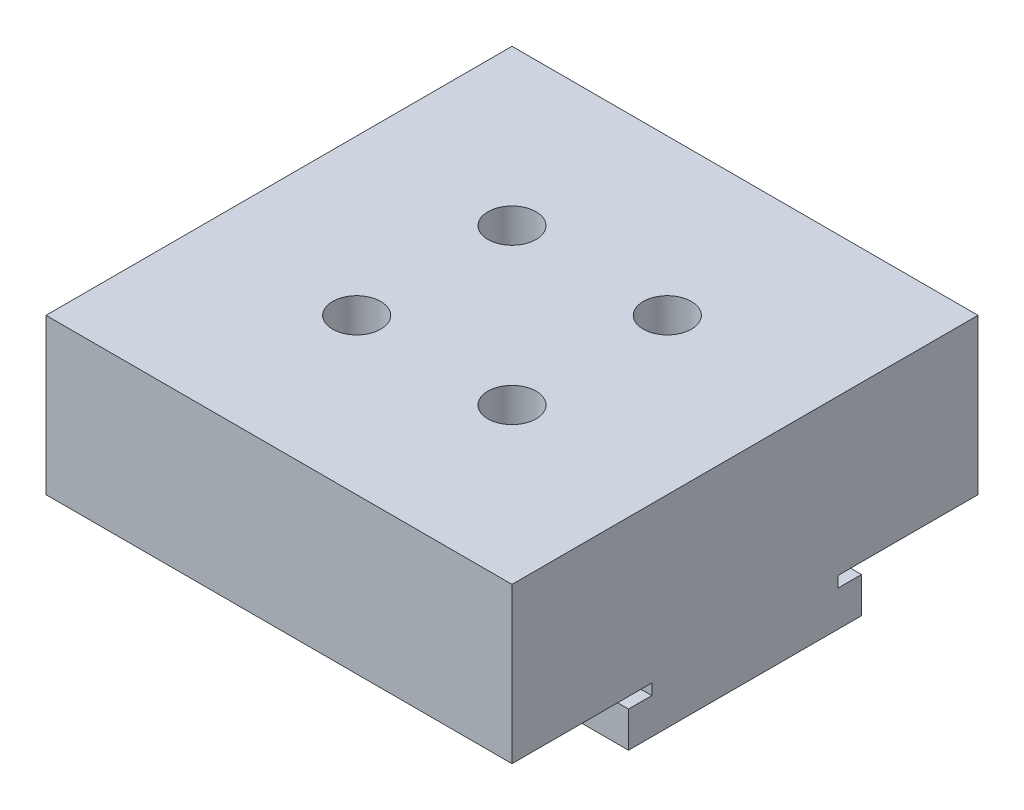
SolidWorks part; units mm, degrees
ref_plane "前视基准面" through (0, 0, 0) normal (0, 0, 1) x (1, 0, 0)
ref_plane "上视基准面" through (0, 0, 0) normal (0, 1, 0) x (1, 0, 0)
ref_plane "右视基准面" through (0, 0, 0) normal (1, 0, 0) x (0, 0, -1)
sketch "草图1" plane through (0, 0, 0) normal (0, 1, 0) x (1, 0, 0)
  line L1 (-5, -5) -> (5, -5) construction
  line L2 (-5, -5) -> (-5, 5) construction
  line L3 (-5, 5) -> (5, 5) construction
  line L4 (5, -5) -> (5, 5) construction
  line L5 (-5, -5) -> (5, 5) construction
  line L6 (-5, 5) -> (5, -5) construction
  line L7 (-15, -15) -> (15, -15)
  line L8 (-15, -15) -> (-15, 15)
  line L9 (-15, 15) -> (15, 15)
  line L10 (15, -15) -> (15, 15)
  line L11 (-15, -15) -> (15, 15) construction
  line L12 (-15, 15) -> (15, -15) construction
  circle A0 centre (-5, 5) radius 1.55
  circle A1 centre (5, 5) radius 1.55
  circle A2 centre (5, -5) radius 1.55
  circle A3 centre (-5, -5) radius 1.55
  point P0 (0, 0)
  point P10 (0, 0)
  dimension "D3" = 3.1
  dimension "D1" = 10
  dimension "D2" = 10
  dimension "D4" = 30
  dimension "D5" = 30
extrude "凸台-拉伸1" add sketch "草图1" along normal blind 10
sketch "草图2" plane through (0, 0, 0) normal (0, -1, 0) x (1, 0, 0)
  circle A0 centre (-5, 5) radius 3.5
  circle A1 centre (5, 5) radius 3.5
  circle A2 centre (5, -5) radius 3.5
  circle A3 centre (-5, -5) radius 3.5
  dimension "D1" = 7
extrude "切除-拉伸1" cut sketch "草图2" against normal blind 3
sketch "草图3" plane through (0, 0, 0) normal (0, -1, 0) x (1, 0, 0)
  line L0 (-15, -15) -> (-15, 15) construction
  line L9 (-15, 7.5) -> (-9, 7.5)
  line L10 (-15, 7.5) -> (-15, -7.5)
  line L11 (-15, -7.5) -> (-9, -7.5)
  line L12 (-9, 7.5) -> (-9, -7.5)
  line L13 (15, 15) -> (15, -15) construction
  line L14 (15, 7.5) -> (9, 7.5)
  line L15 (15, 7.5) -> (15, -7.5)
  line L16 (15, -7.5) -> (9, -7.5)
  line L17 (9, 7.5) -> (9, -7.5)
  line L18 (0, 0) -> (-13.7355, 0) construction
  point P14 (-9, 0)
  dimension "D1" = 15
  dimension "D2" = 6
  dimension "D3" = 6
extrude "凸台-拉伸3" add sketch "草图3" along normal blind 3
sketch "草图5" plane through (-15, 0, 0) normal (-1, 0, 0) x (0, 0, 1)
  line L1 (-7.5, 0) -> (-6, 0)
  line L2 (-7.5, 0) -> (-7.5, -0.7)
  line L3 (-7.5, -0.7) -> (-6, -0.7)
  line L4 (-6, 0) -> (-6, -0.7)
  line L5 (7.5, 0) -> (6, 0)
  line L6 (7.5, 0) -> (7.5, -0.7)
  line L7 (7.5, -0.7) -> (6, -0.7)
  line L8 (6, 0) -> (6, -0.7)
  dimension "D1" = 0.7
  dimension "D2" = 1.5
  dimension "D3" = 1.5
  dimension "D5" = 0.7
extrude "切除-拉伸3" cut sketch "草图5" against normal through all
